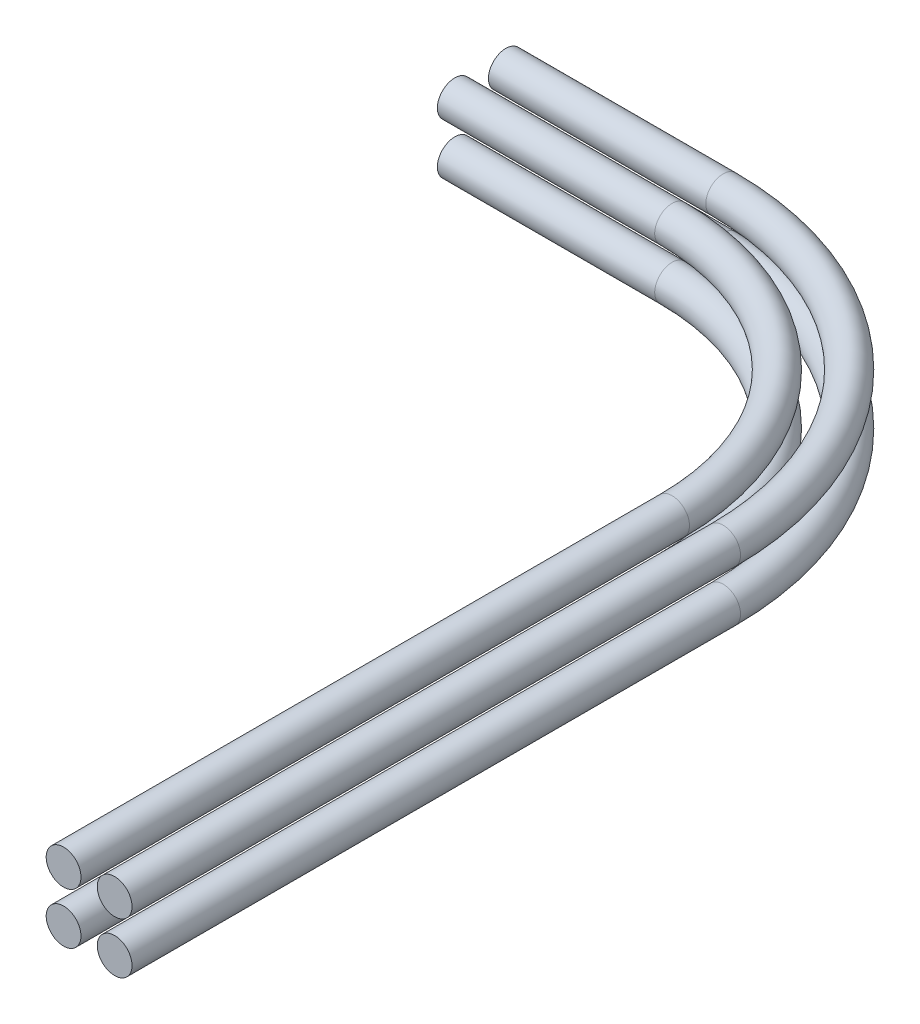
SolidWorks part; units mm, degrees
ref_plane "Front Plane" through (0, 0, 0) normal (0, 0, 1) x (1, 0, 0)
ref_plane "Top Plane" through (0, 0, 0) normal (0, 1, 0) x (1, 0, 0)
ref_plane "Right Plane" through (0, 0, 0) normal (1, 0, 0) x (0, 0, -1)
sketch "Sketch1" plane through (0, 0, 0) normal (0, 1, 0) x (1, 0, 0)
  line L0 (0, 0) -> (20, 0)
  line L1 (48, -28) -> (48, -84)
  line L2 (0, -4.7) -> (20, -4.7)
  line L3 (43.3, -28) -> (43.3, -84)
  line L4 (0, -4.7) -> (0, 0) construction
  line L5 (48, -84) -> (43.3, -84) construction
  line L6 (20, 0) -> (20, -4.7) construction
  line L7 (43.3, -28) -> (48, -28) construction
  arc A0 (20, -4.7) -> (43.3, -28) centre (20, -28) cw
  arc A1 (20, 0) -> (48, -28) centre (20, -28) cw
  point P11 (48, 0)
  dimension "D4" = 28
  dimension "D1" = 4.7
  dimension "D2" = 20
  dimension "D3" = 84
ref_plane "Plane1" through (0, 0, 0) normal (1, 0, 0) x (0, 0, -1)
sketch "Sketch2" plane through (0, 0, 0) normal (1, 0, 0) x (0, 0, -1)
  circle A0 centre (0, 0) radius 1.6
  circle A1 centre (-4.7, 0) radius 1.6
  dimension "D1" = 3.2
sweep "Sweep1" add profiles "Sketch2" path "Sketch1"
sketch "Sketch3" plane through (0, 0, 0) normal (1, 0, 0) x (0, 0, -1)
  line L0 (0, 0) -> (0, 4.7) construction
  dimension "D1" = 4.7
pattern_linear "LPattern1" count 2 spacing 4.7 along (0, 1, 0) of "Sweep1"
